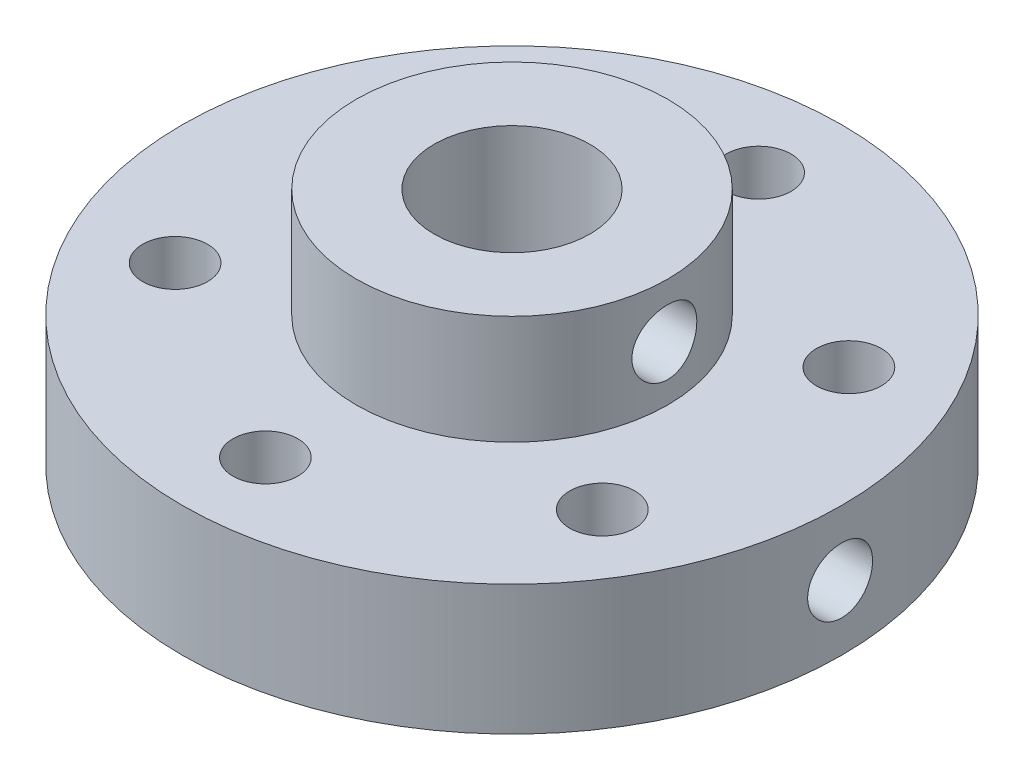
SolidWorks part; units mm, degrees
ref_plane "Front Plane" through (0, 0, 0) normal (0, 0, 1) x (1, 0, 0)
ref_plane "Top Plane" through (0, 0, 0) normal (0, 1, 0) x (1, 0, 0)
ref_plane "Right Plane" through (0, 0, 0) normal (1, 0, 0) x (0, 0, -1)
sketch "Sketch1" plane through (0, 0, 0) normal (0, 1, 0) x (1, 0, 0)
  circle A0 centre (0, 0) radius 12.7
  dimension "D1" = 25.4
extrude "Boss-Extrude1" add sketch "Sketch1" along normal blind 5
sketch "Sketch2" plane through (0, 5, 0) normal (0, 1, 0) x (1, 0, 0)
  circle A0 centre (0, 0) radius 6
  dimension "D1" = 12
extrude "Boss-Extrude2" add sketch "Sketch2" along normal blind 4.2
sketch "Sketch3" plane through (0, 9.2, 0) normal (0, 1, 0) x (1, 0, 0)
  circle A0 centre (0, 0) radius 3
  dimension "D1" = 6
extrude "Cut-Extrude1" cut sketch "Sketch3" against normal through all
hole_wizard "Tap Drill for M3 Tap1" positions "Sketch4" profile "Sketch6" hole size "M3" standard "DIN" end condition through all
sketch "Sketch4" plane through (0, 5, 0) normal (0, 1, 0) x (1, 0, 0)
  circle A0 centre (0, 0) radius 9.5 construction
  point P5 (0, 9.5)
  point P11 (8.2272, 4.75)
  point P12 (8.2272, -4.75)
  point P13 (0, -9.5)
  point P14 (-8.2272, -4.75)
  point P15 (-8.2272, 4.75)
  dimension "D1" = 19
  dimension "D2" = 6
sketch "Sketch6" plane through (-8.2272, 5, -4.75) normal (1, 0, 0) x (0, 0, 1)
  line L0 (0, 0) -> (0, 5)
  line L1 (0, 5) -> (1.25, 5)
  line L2 (1.25, 5) -> (1.25, 0)
  line L5 (1.25, 0) -> (0, 0)
  line L11 (0, -6.35) -> (0, 107.95) construction
  dimension "Thru Hole Dia." = 2.5
  dimension "Thru Hole Depth" = 5
hole_wizard "Tap Drill for M3 Tap2" positions "Sketch7" profile "Sketch8" hole size "M3" standard "DIN"
sketch "Sketch7" plane through (0, 0, 0) normal (1, 0, 0) x (0, 0, -1)
  line L0 (0, 0) -> (0, 2.5)
  line L1 (0, 2.5) -> (0, 7.1)
  line L3 (6, 9.2) -> (-6, 9.2) construction
  point P0 (0, 2.5)
  point P2 (0, 7.1)
  dimension "D1" = 2.1
  dimension "D2" = 2.5
sketch "Sketch8" plane through (0, 2.5, 0) normal (0, 1, 0) x (0, 0, 1)
  line L0 (0, 0) -> (0, 12.7)
  line L1 (0, 12.7) -> (1.25, 12.7)
  line L2 (1.25, 12.7) -> (1.25, 0)
  line L5 (1.25, 0) -> (0, 0)
  line L11 (0, -6.35) -> (0, 107.95) construction
  dimension "Thru Hole Dia." = 2.5
  dimension "Thru Hole Depth" = 12.7
